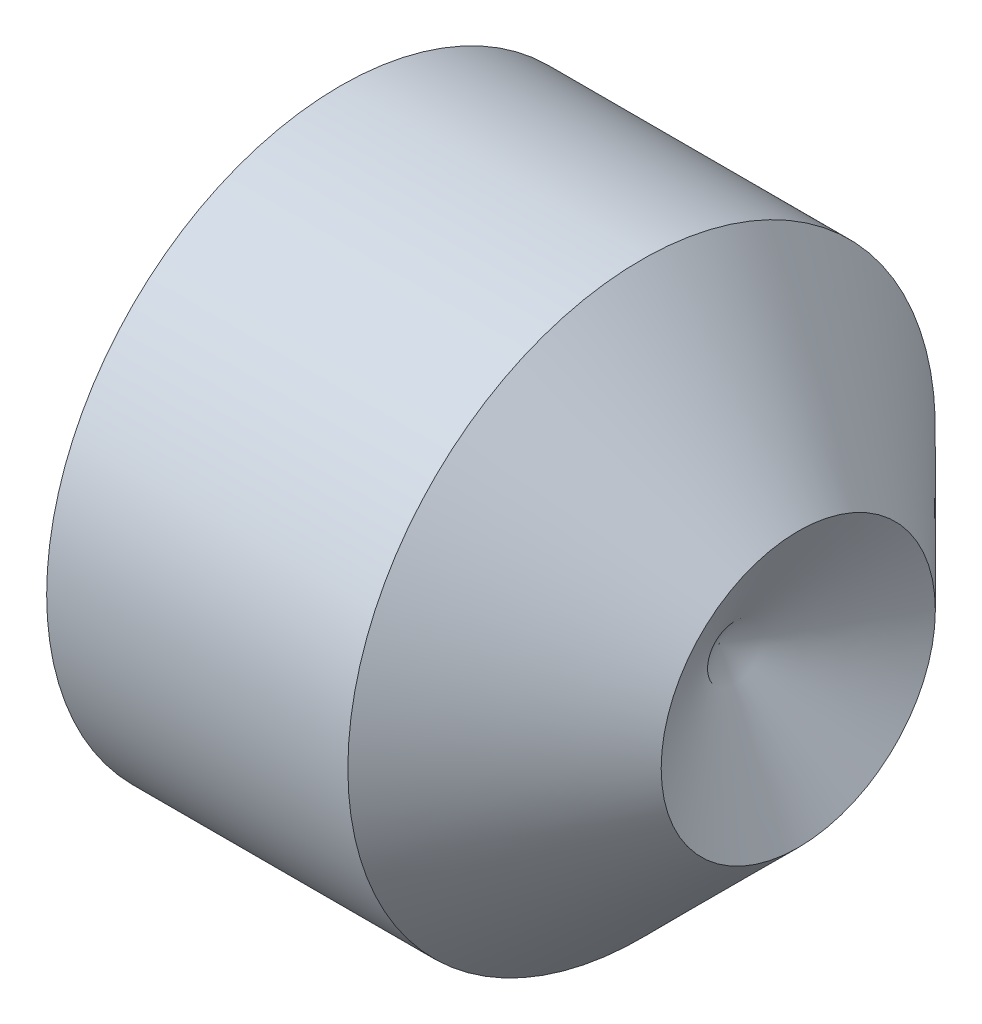
SolidWorks part; units mm, degrees
revolve "BaseBody" add sketch "BodySke" angle 360 about L5
sketch "BodySke" plane through (0, 0, 0) normal (0, 0, 1) x (1, 0, 0)
  line L0 (0, 0) -> (0, 1.2195)
  line L1 (0, 1.2195) -> (0.1619, 1.5)
  line L2 (0.1619, 1.5) -> (1.7, 1.5)
  line L3 (1.7, 1.5) -> (2.5, 0.7)
  line L4 (2.0959, 0) -> (0, 0)
  line L5 (-12.7, 0) -> (88.9, 0) construction
  line L6 (2.0959, 0) -> (2.5, 0.7)
  line L7 (2.5, 0.7) -> (2.5, 10.225) construction
  line L8 (0, -1.2195) -> (0.1619, -1.5) construction
  line L9 (2.0959, 0) -> (2.5, -0.7) construction
  line L10 (1.7, -1.5) -> (2.5, -0.7) construction
  line L11 (0.25, 15.875) -> (0.25, -3.175) construction
  dimension "Diameter" = 3
  dimension "Drive_ch_ang" = 60
  dimension "Minor_dia" = 2.439
  dimension "Cup_ang" = 120
  dimension "Cup_dia" = 1.4
  dimension "Length" = 2.5
  dimension "Cup_nose_ang" = 45
  dimension "Advance" = 0.5
cosmetic thread "ThreadCosmetic" [suppressed] parameters "Thread_minor"=2.439
material "PA Type 6"
ref_plane "Plane1" through (0, 0, 0) normal (0, 0, 1) x (1, 0, 0)
ref_plane "Plane2" through (0, 0, 0) normal (0, 1, 0) x (1, 0, 0)
ref_plane "Plane3" through (0, 0, 0) normal (1, 0, 0) x (0, 0, -1)
sketch "Sketch2" plane through (0, 0, 0) normal (-1, 0, 0) x (0, 0, 1)
  line L0 (0.433, 0.75) -> (-0.433, 0.75)
  line L1 (-0.433, 0.75) -> (-0.866, 0)
  line L2 (0.433, 0.75) -> (0.866, 0)
  line L3 (0.433, -0.75) -> (0.866, 0)
  line L4 (0.433, -0.75) -> (-0.433, -0.75)
  line L5 (-0.433, -0.75) -> (-0.866, 0)
  dimension "Hex_size" = 1.5
  dimension "D2" = 0.75
  dimension "D3" = 0.75
extrude "Hex" cut sketch "Sketch2" against normal blind 1.2
sketch "ThdSchSke" plane through (0, 0, 0) normal (0, 0, 1) x (1, 0, 0)
  line L0 (0.1619, -1.2195) -> (-0.0345, -1.5)
  line L1 (0.1619, -1.2195) -> (0.3584, -1.5)
  line L2 (0.3584, -1.5) -> (0.3584, -1.875)
  line L3 (-3.175, 0) -> (5.1513, 0) construction
  line L4 (0.1619, 1.5) -> (0.1619, -1.5) construction
  line L5 (0.3584, -1.875) -> (-0.0345, -1.875)
  line L6 (-0.0345, -1.875) -> (-0.0345, -1.5)
  dimension "Thread_minor" = 2.439
  dimension "Diameter" = 3
revolve "ThreadSchematic" [suppressed] cut sketch "ThdSchSke" angle 360 about L3
pattern_linear "ThdSchPat" [suppressed]
equation "\"D2@Sketch2\" = \"Hex_size@Sketch2\" / 2"
equation "\"D3@Sketch2\" = \"Hex_size@Sketch2\" / 2"
equation "\"Thread_minor@ThreadCosmetic\" = \"Minor_dia@BodySke\""
equation "\"Thread_minor@ThdSchSke\" = \"Thread_minor@ThreadCosmetic\""
equation "\"Diameter@ThdSchSke\" = \"Diameter@BodySke\""
equation "\"Overcut@ThdSchSke\" = \"Diameter@BodySke\" * 1.25"
equation "\"Num_threads@ThdSchPat\" = int( (\"Length@BodySke\" - ( ( ( \"Diameter@BodySke\" - \"Minor_dia@BodySke\" ) * 0.5 ) / tan( \"Drive_ch_ang@BodySke\" * 0.017453292 ) ) - ( ( ( \"Diameter@BodySke\" - \"Cup_dia@BodySke\" ) * 0.5 ) * tan( \"Cup_nose_ang@BodySke\" * 0.017453292 ) ) ) / \"Advance@BodySke\" + 0.999 )  + 1"
equation "\"Advance@ThdSchPat\" = (\"Length@BodySke\" - ( ( ( \"Diameter@BodySke\" - \"Minor_dia@BodySke\" ) * 0.5 ) / tan( \"Drive_ch_ang@BodySke\" * 0.017453292 ) ) - ( ( ( \"Diameter@BodySke\" - \"Cup_dia@BodySke\" ) * 0.5 ) * tan( \"Cup_nose_ang@BodySke\" * 0.017453292 ) ) ) /  (\"Num_threads@ThdSchPat\" - 1) 'relax it"
equation "' \"Num_threads@ThdSchPat\" = \"Num_threads@ThdSchPat\" - sgn( \"Num_threads@ThdSchPat\" - 1) '---chamfered tips only---"
